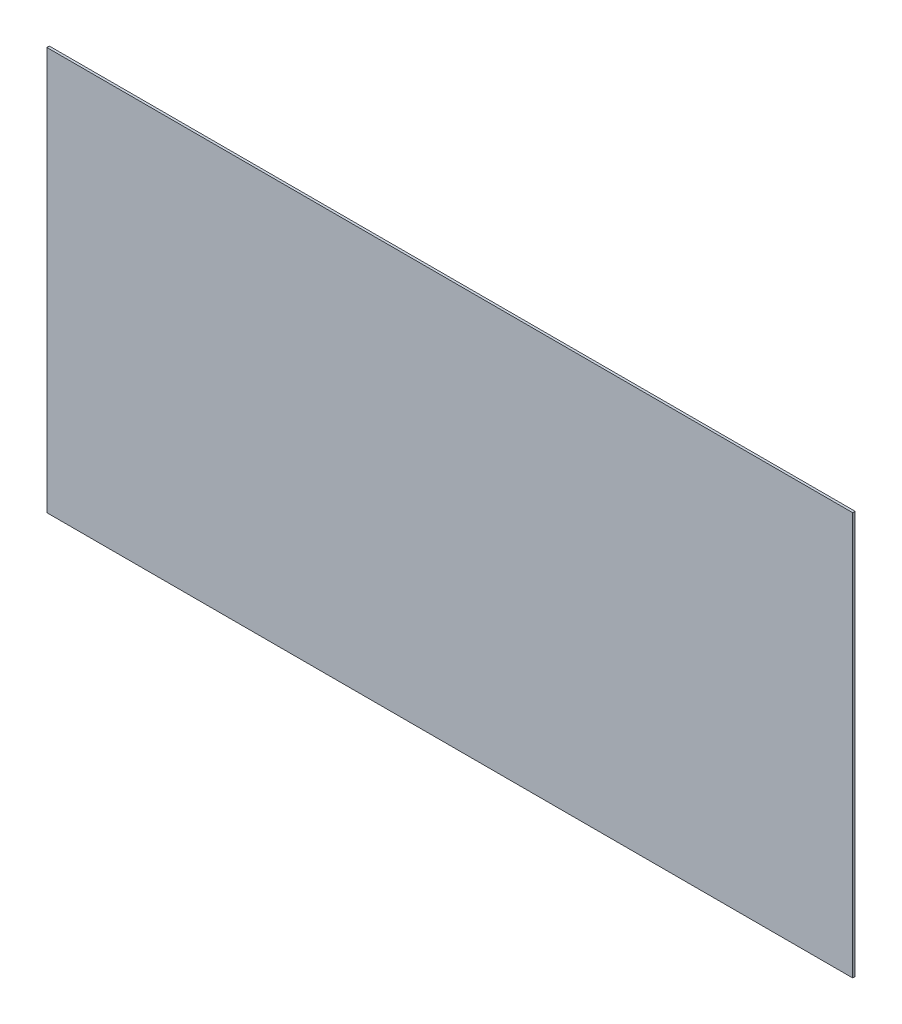
SolidWorks part; units mm, degrees
material "Acrylic (Medium-high impact)"
ref_plane "Front Plane" through (0, 0, 0) normal (0, 0, 1) x (1, 0, 0)
ref_plane "Top Plane" through (0, 0, 0) normal (0, 1, 0) x (1, 0, 0)
ref_plane "Right Plane" through (0, 0, 0) normal (1, 0, 0) x (0, 0, -1)
sketch "Sketch1" plane through (0, 0, 0) normal (0, 0, 1) x (1, 0, 0)
  line L1 (-914.4, -457.2) -> (914.4, -457.2)
  line L2 (-914.4, -457.2) -> (-914.4, 457.2)
  line L3 (-914.4, 457.2) -> (914.4, 457.2)
  line L4 (914.4, -457.2) -> (914.4, 457.2)
  line L5 (-914.4, -457.2) -> (914.4, 457.2) construction
  line L6 (-914.4, 457.2) -> (914.4, -457.2) construction
  point P0 (0, 0)
  dimension "D1" = 914.4
  dimension "D2" = 1828.8
extrude "Boss-Extrude1" add sketch "Sketch1" along normal blind 5.588
